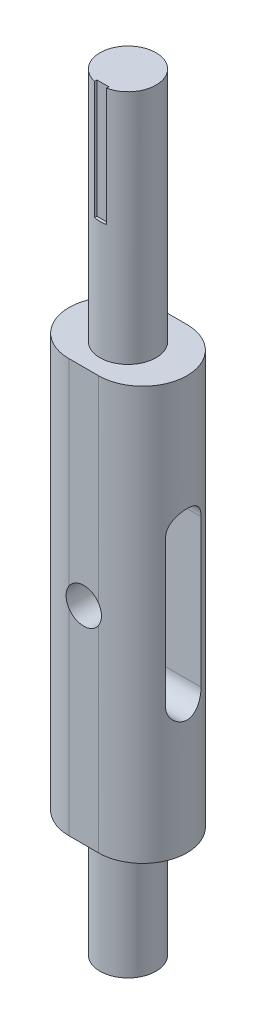
SolidWorks part; units mm, degrees
ref_plane "Piano frontale" through (0, 0, 0) normal (0, 0, 1) x (1, 0, 0)
ref_plane "Piano superiore" through (0, 0, 0) normal (0, 1, 0) x (1, 0, 0)
ref_plane "Piano destro" through (0, 0, 0) normal (1, 0, 0) x (0, 0, -1)
sketch "Schizzo1" plane through (0, 0, 0) normal (0, 1, 0) x (1, 0, 0)
  line L0 (-5, 0) -> (5, 0) construction
  line L1 (-5, 15) -> (5, 15)
  line L2 (-5, -15) -> (5, -15)
  arc A0 (-5, 15) -> (-5, -15) centre (-5, 0) ccw
  arc A1 (5, -15) -> (5, 15) centre (5, 0) ccw
  point P3 (0, 0)
  dimension "D1" = 10
  dimension "D2" = 30
extrude "Estrusione-Estrusione1" add sketch "Schizzo1" along normal blind 260
sketch "Schizzo2" plane through (0, 0, 0) normal (0, -1, 0) x (1, 0, 0)
  line L2 (-5, -15) -> (5, -15)
  line L3 (5, 15) -> (-5, 15)
  line L4 (-5, -15) -> (5, -15)
  line L5 (5, 15) -> (-5, 15)
  circle A0 centre (0, 0) radius 9.5
  arc A3 (-5, 15) -> (-5, -15) centre (-5, 0) ccw
  arc A4 (5, -15) -> (5, 15) centre (5, 0) ccw
  arc A5 (-5, 15) -> (-5, -15) centre (-5, 0) ccw
  arc A6 (5, -15) -> (5, 15) centre (5, 0) ccw
  dimension "D1" = 19
  dimension "D2" = 0
extrude "Taglio-Estrusione1" cut sketch "Schizzo2" against normal blind 40
sketch "Schizzo3" plane through (0, 260, 0) normal (0, 1, 0) x (1, 0, 0)
  line L2 (-5, -15) -> (5, -15)
  line L3 (5, 15) -> (-5, 15)
  line L4 (-5, -15) -> (5, -15)
  line L5 (5, 15) -> (-5, 15)
  circle A0 centre (0, 0) radius 9.5
  arc A3 (-5, 15) -> (-5, -15) centre (-5, 0) ccw
  arc A4 (5, -15) -> (5, 15) centre (5, 0) ccw
  arc A5 (-5, 15) -> (-5, -15) centre (-5, 0) ccw
  arc A6 (5, -15) -> (5, 15) centre (5, 0) ccw
  dimension "D1" = 19
  dimension "D2" = 0
extrude "Taglio-Estrusione2" cut sketch "Schizzo3" against normal blind 80
sketch "Schizzo4" plane through (0, 0, 15) normal (-1, 0, 0) x (0, 0, 1)
  line L0 (-15, 135) -> (-15, 85) construction
  line L1 (-9, 135) -> (-9, 85)
  line L2 (-21, 135) -> (-21, 85)
  line L3 (0, 180) -> (-30, 180) construction
  arc A0 (-9, 135) -> (-21, 135) centre (-15, 135) ccw
  arc A1 (-21, 85) -> (-9, 85) centre (-15, 85) ccw
  point P3 (-15, 110)
  dimension "D1" = 50
  dimension "D2" = 95
  dimension "D3" = 12
extrude "Taglio-Estrusione3" cut sketch "Schizzo4" against normal through all both and the other way through all
sketch "Schizzo5" plane through (0, 0, -15) normal (0, 0, -1) x (-1, 0, 0)
  line L0 (-5, 180) -> (5, 180) construction
  line L1 (5, 180) -> (5, 40) construction
  circle A0 centre (0, 110) radius 6
  dimension "D1" = 12
  dimension "D2" = 70
  dimension "D3" = 5
extrude "Taglio-Estrusione4" cut sketch "Schizzo5" against normal blind 80
sketch "Schizzo6" plane through (0, 260, 0) normal (0, 1, 0) x (1, 0, 0)
  line L0 (-2, -9.2871) -> (-2, -8.5)
  line L1 (-2, -8.5) -> (2, -8.5)
  line L2 (2, -8.5) -> (2, -9.2871)
  circle A1 centre (0, 0) radius 9.5
  arc A2 (-2, -9.2871) -> (2, -9.2871) centre (0, 0) ccw
  point P5 (0, -8.5)
  dimension "D2" = 8.5
  dimension "D3" = 4
  dimension "D1" = 0
extrude "Taglio-Estrusione5" cut sketch "Schizzo6" against normal blind 40
